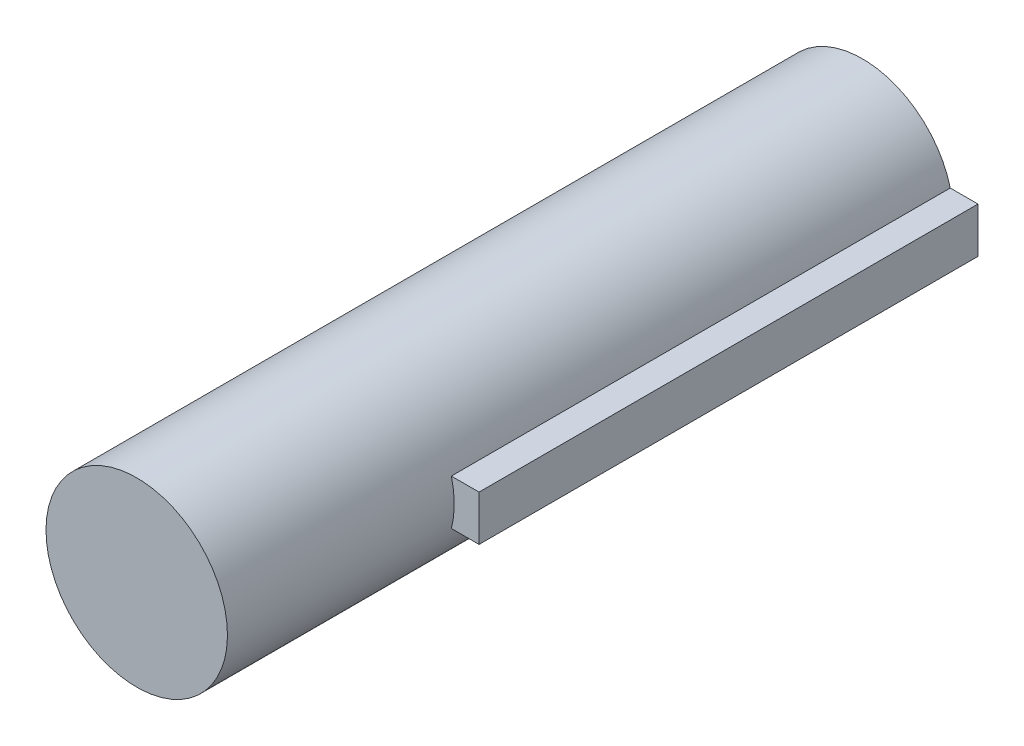
SolidWorks part; units mm, degrees
ref_plane "Front Plane" through (0, 0, 0) normal (0, 0, 1) x (1, 0, 0)
ref_plane "Top Plane" through (0, 0, 0) normal (0, 1, 0) x (1, 0, 0)
ref_plane "Right Plane" through (0, 0, 0) normal (1, 0, 0) x (0, 0, -1)
sketch "Sketch1" plane through (0, 0, 0) normal (0, 0, 1) x (1, 0, 0)
  circle A0 centre (0, 0) radius 20
  dimension "D1" = 40
extrude "Boss-Extrude1" add sketch "Sketch1" along normal blind 160
sketch "Sketch2" plane through (0, 0, 0) normal (0, 0, -1) x (-1, 0, 0)
  line L0 (-20, 0) -> (20, 0) construction
  line L1 (0, 20) -> (0, -20) construction
  line L3 (-25.4782, 5) -> (-19.3649, 5)
  line L4 (-25.4782, 5) -> (-25.4782, -5)
  line L5 (-25.4782, -5) -> (-19.3649, -5)
  line L7 (-25.4782, 5) -> (-20, 0) construction
  line L8 (-25.4782, -5) -> (-20, 0) construction
  circle A0 centre (0, 0) radius 20 construction
  circle A1 centre (0, 0) radius 20
  point P7 (-22.4216, -5)
  circle M8 centre (0, 0) radius 20
  dimension "D1" = 10
  dimension "D2" = 5
extrude "Boss-Extrude2" add sketch "Sketch2" against normal blind 110 contours L4 L5 L3 M8
